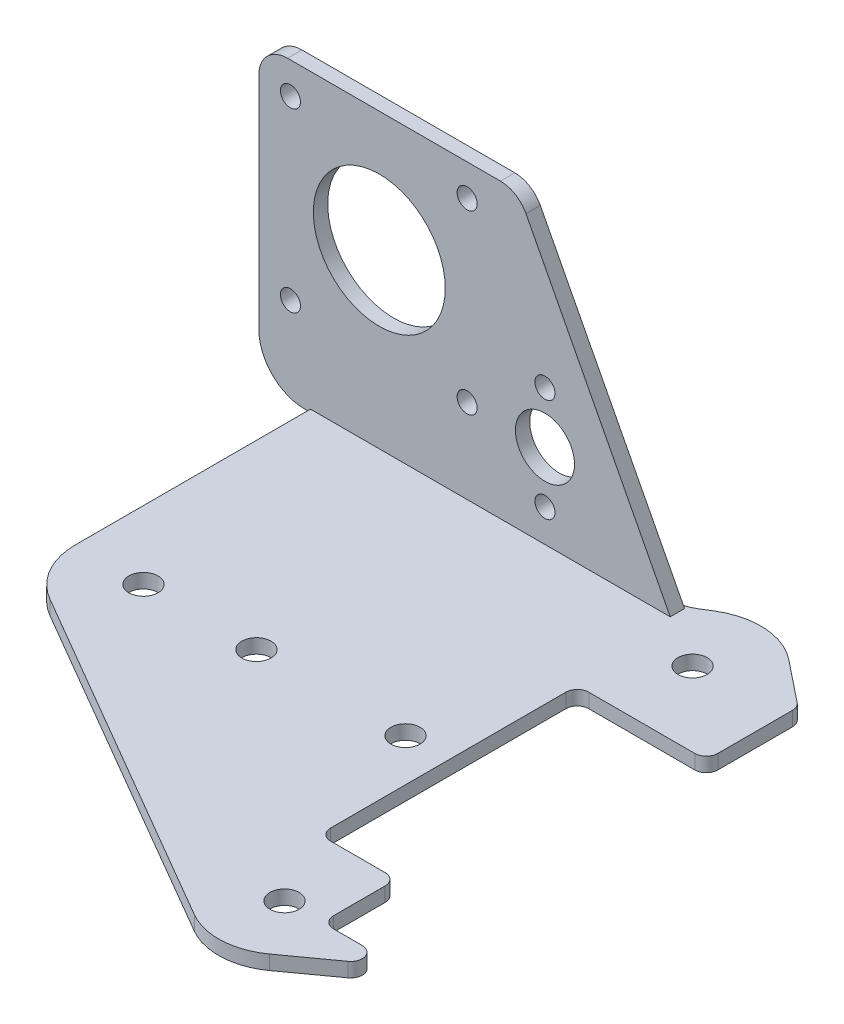
SolidWorks part; units mm, degrees
material "Cast Alloy Steel"
ref_plane "Front Plane" through (0, 0, 0) normal (0, 0, 1) x (1, 0, 0)
ref_plane "Top Plane" through (0, 0, 0) normal (0, 1, 0) x (1, 0, 0)
ref_plane "Right Plane" through (0, 0, 0) normal (1, 0, 0) x (0, 0, -1)
sketch "Sketch2" plane through (0, 0, 0) normal (0, 1, 0) x (1, 0, 0)
  line L0 (0, 0) -> (0, -43.53)
  line L1 (0, 0) -> (59.81, 0)
  line L2 (5.9638, -53.9013) -> (66.2124, -88.9668)
  line L3 (78.7306, -88.3502) -> (86.6831, -82.6062)
  line L4 (85.5121, -78.9849) -> (80.5121, -78.9849)
  line L5 (78.5121, -76.9849) -> (78.5121, -67.9849)
  line L6 (76.5121, -65.9849) -> (67.0121, -65.9849)
  line L7 (65.0121, -63.9849) -> (65.0121, -22.9849)
  line L8 (67.0121, -20.9849) -> (85.5121, -20.9849)
  line L9 (87.5121, -18.9849) -> (87.5121, -5.9549)
  line L10 (86.759, -4.3912) -> (79.4957, 1.4008)
  line L11 (63.9804, 1.173) -> (65.7584, 2.2592)
  arc A0 (0, -43.53) -> (5.9638, -53.9013) centre (12, -43.53) ccw
  arc A1 (66.2124, -88.9668) -> (78.7306, -88.3502) centre (71.9971, -79.0277) ccw
  arc A2 (86.6831, -82.6062) -> (85.5121, -78.9849) centre (85.5121, -80.9849) ccw
  arc A3 (80.5121, -78.9849) -> (78.5121, -76.9849) centre (80.5121, -76.9849) cw
  arc A4 (78.5121, -67.9849) -> (76.5121, -65.9849) centre (76.5121, -67.9849) ccw
  arc A5 (67.0121, -65.9849) -> (65.0121, -63.9849) centre (67.0121, -63.9849) cw
  arc A6 (65.0121, -22.9849) -> (67.0121, -20.9849) centre (67.0121, -22.9849) cw
  arc A7 (85.5121, -20.9849) -> (87.5121, -18.9849) centre (85.5121, -18.9849) ccw
  arc A8 (87.5121, -5.9549) -> (86.759, -4.3912) centre (85.5121, -5.9549) ccw
  arc A9 (59.81, 0) -> (63.9804, 1.173) centre (59.81, 8) ccw
  arc A10 (79.4957, 1.4008) -> (65.7584, 2.2592) centre (72.014, -7.9813) ccw
  circle A11 centre (71.9971, -79.0277) radius 2.55
  circle A12 centre (11.9, -43.53) radius 2.55
  circle A13 centre (31.6, -43.53) radius 2.55
  circle A14 centre (57.6, -43.53) radius 2.55
  circle A15 centre (72.1121, -7.9849) radius 2.55
  dimension "D3" = 12
  dimension "D6" = 11.5
  dimension "D9" = 2
  dimension "D11" = 2
  dimension "D12" = 2
  dimension "D15" = 2
  dimension "D17" = 2
  dimension "D19" = 2
  dimension "D21" = 2
  dimension "D24" = 12
  dimension "D25" = 8
  dimension "D26" = 5.1
  dimension "D27" = 5.1
  dimension "D28" = 5.1
  dimension "D29" = 5.1
  dimension "D30" = 5.1
  dimension "D32" = 13
  dimension "D33" = 11.9
  dimension "D34" = 43.53
  dimension "D1" = 43.53
  dimension "D2" = 59.81
  dimension "D4" = 69.71
  dimension "D5" = 120.2
  dimension "D7" = 9.81
  dimension "D8" = 54.16
  dimension "D10" = 5
  dimension "D13" = 9
  dimension "D14" = 9.5
  dimension "D16" = 41
  dimension "D18" = 18.5
  dimension "D20" = 13.03
  dimension "D22" = 9.29
  dimension "D23" = 128.57
  dimension "D31" = 15.4
  dimension "D35" = 19.6
  dimension "D36" = 26
extrude "Boss-Extrude1" add sketch "Sketch2" along normal blind 2.5
sketch "Sketch3" plane through (0, 0, 0) normal (0, 0, 1) x (1, 0, 0)
  line L0 (0, 2) -> (-1, 2)
  line L1 (-9, 10) -> (-9, 48.5)
  line L2 (33.14, 53.5) -> (17.1168, 53.5)
  line L3 (37.5747, 50.8095) -> (62.9647, 2.0565)
  line L5 (-4, 53.5) -> (8.5451, 53.5)
  line L6 (8.5451, 53.5) -> (17.1168, 53.5)
  line L7 (59.81, 2.5) -> (0, 2.5) construction
  line L8 (0, 2.5) -> (0, 0) construction
  line L9 (62.9647, 2.0565) -> (0, 2)
  arc A0 (-1, 2) -> (-9, 10) centre (-1, 10) cw
  arc A1 (33.14, 53.5) -> (37.5747, 50.8095) centre (33.14, 48.5) cw
  arc A2 (-9, 48.5) -> (-4, 53.5) centre (-4, 48.5) cw
  circle A3 centre (12, 32.5) radius 11.5
  circle A4 centre (40.8847, 17.1867) radius 5.15
  circle A5 centre (40.8847, 26.1867) radius 1.75
  circle A6 centre (40.8847, 8.1867) radius 1.75
  circle A8 centre (-3.5, 48) radius 1.75
  circle A9 centre (27.3133, 48) radius 1.75
  circle A10 centre (27.3133, 17.1867) radius 1.75
  circle A11 centre (-3.5, 17.1867) radius 1.75
  point P40 (11.9066, 32.5934)
  dimension "D2" = 8
  dimension "D5" = 5
  dimension "D4" = 5
  dimension "D12" = 3.5
  dimension "D13" = 23
  dimension "D14" = 10.3
  dimension "D15" = 22.08
  dimension "D16" = 3.5
  dimension "D17" = 3.5
  dimension "D18" = 21
  dimension "D19" = 15.15
  dimension "D21" = 5.5
  dimension "D22" = 5.5
  dimension "D24" = 9
  dimension "D26" = 5.5
  dimension "D1" = 1
  dimension "D3" = 38.5
  dimension "D6" = 117.51
  dimension "D7" = 37.14
  dimension "D8" = 0.5
  dimension "D9" = 54.9682
  dimension "D10" = 8.5451
  dimension "D11" = 17.1168
  dimension "D20" = 21
  dimension "D25" = 9
  dimension "D23" = 4
extrude "Boss-Extrude2" add sketch "Sketch3" along normal blind 2.5
